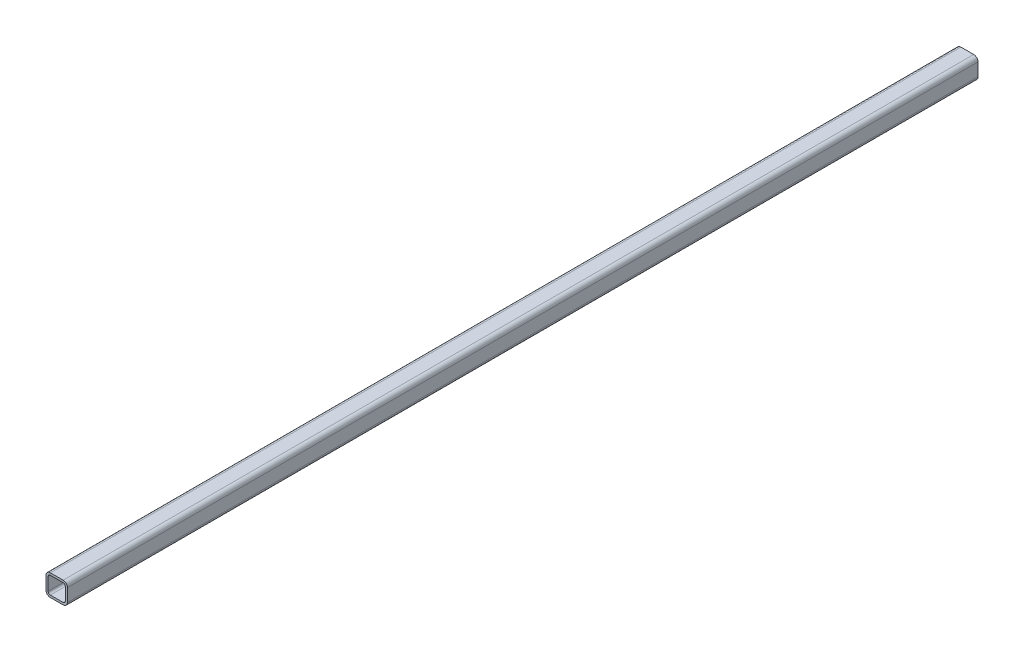
SolidWorks part; units mm, degrees
ref_plane "Front Plane" through (0, 0, 0) normal (0, 0, 1) x (1, 0, 0)
ref_plane "Top Plane" through (0, 0, 0) normal (0, 1, 0) x (1, 0, 0)
ref_plane "Right Plane" through (0, 0, 0) normal (1, 0, 0) x (0, 0, -1)
sketch "Sketch1" plane through (0, 0, 0) normal (0, 1, 0) x (1, 0, 0)
  line L1 (854.075, -850.011) -> (-854.075, -850.011)
  line L2 (854.075, -850.011) -> (854.075, 850.011)
  line L3 (854.075, 850.011) -> (-854.075, 850.011)
  line L4 (-854.075, -850.011) -> (-854.075, 850.011)
  line L5 (854.075, -850.011) -> (-854.075, 850.011) construction
  line L6 (854.075, 850.011) -> (-854.075, -850.011) construction
  point P0 (0, 0)
  dimension "D1" = 1708.15
  dimension "D2" = 1700.022
sketch3d "3DSketch1"
  line L0 (-854.075, 0, -850.011) -> (854.075, 0, -850.011)
  line L1 (854.075, 0, -850.011) -> (854.075, 0, 850.011)
  line L2 (854.075, 0, 850.011) -> (-854.075, 0, 850.011)
  line L3 (-854.075, 0, 850.011) -> (-854.075, 0, -850.011)
  line L4 (0, 0, -850.011) -> (0, 0, 850.011)
other "Square tube 40 X 40 X 4(2)"
ref_plane "Plane5" through (0, 0, -850.011) normal (0, 0, 1) x (1, 0, 0)
sketch "Sketch13" plane through (0, 0, -850.011) normal (0, 0, 1) x (1, 0, 0)
  line L0 (-12, -16) -> (12, -16)
  line L1 (-16, -12) -> (-16, 12)
  line L2 (12, 16) -> (-12, 16)
  line L3 (16, 12) -> (16, -12)
  line L4 (-12, -20) -> (12, -20)
  line L5 (-20, -12) -> (-20, 12)
  line L6 (12, 20) -> (-12, 20)
  line L7 (20, 12) -> (20, -12)
  arc A0 (20, 12) -> (12, 20) centre (12, 12) ccw
  arc A1 (12, -20) -> (20, -12) centre (12, -12) ccw
  arc A2 (-20, -12) -> (-12, -20) centre (-12, -12) ccw
  arc A3 (-12, 20) -> (-20, 12) centre (-12, 12) ccw
  arc A4 (-12, 16) -> (-16, 12) centre (-12, 12) ccw
  arc A5 (16, 12) -> (12, 16) centre (12, 12) ccw
  arc A6 (12, -16) -> (16, -12) centre (12, -12) ccw
  arc A7 (-16, -12) -> (-12, -16) centre (-12, -12) ccw
  point P0 (-20, 0)
  point P1 (20, 0)
  point P2 (0, 20)
  point P3 (0, -20)
  point P4 (0, 0)
  point P5 (-20, -20)
  point P6 (20, -20)
  point P7 (20, 20)
  point P8 (-20, 20)
  point P33 (0, 0)
  dimension "D1" = 8
  dimension "Thickness" = 4
  dimension "V_leg" = 40
